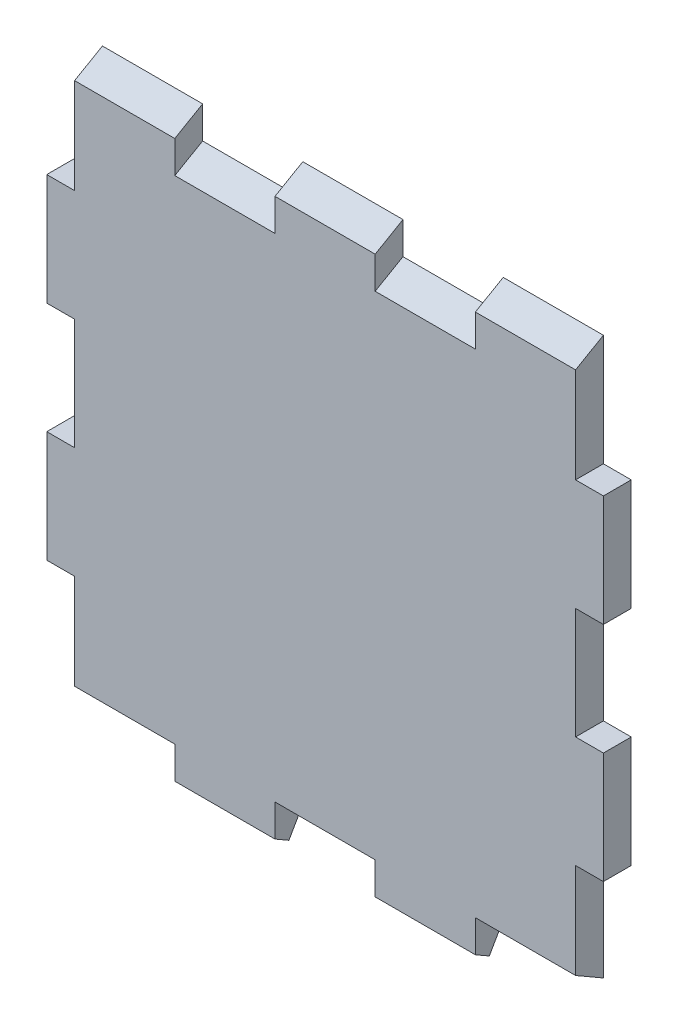
SolidWorks part; units mm, degrees
ref_plane "Front Plane" through (0, 0, 0) normal (0, 0, 1) x (1, 0, 0)
ref_plane "Top Plane" through (0, 0, 0) normal (0, 1, 0) x (1, 0, 0)
ref_plane "Right Plane" through (0, 0, 0) normal (1, 0, 0) x (0, 0, -1)
sketch "Esquisse1" plane through (0, 0, 0) normal (0, 0, 1) x (1, 0, 0)
  line L1 (0, 0) -> (-90, 0)
  line L2 (0, 0) -> (0, -100)
  line L3 (0, -100) -> (-90, -100)
  line L4 (-90, 0) -> (-90, -100)
  line L5 (-45, -100) -> (-45, 0) construction
  line L6 (0, -50) -> (-90, -50) construction
  point P84 (-45, -50)
  dimension "D1" = 100
  dimension "D2" = 90
extrude "Boss.-Extru.3" add sketch "Esquisse1" along normal blind 5
sketch "Esquisse5" plane through (0, 0, 0) normal (1, 0, 0) x (0, 0, -1)
  line L0 (0, 0) -> (-5, 0)
  line L1 (-5, -100) -> (-5, 0) construction
  line L2 (-5, 0) -> (-5, -5.7735)
  line L3 (-86.6025, -52.8868) -> (-69.282, -42.8868) construction
  line L4 (-5, -5.7735) -> (0, -2.8868)
  line L5 (0, -100) -> (0, 0) construction
  line L6 (0, -2.8868) -> (0, 0)
extrude "Enlèv. mat.-Extru.3" cut sketch "Esquisse5" against normal through all
sketch "Esquisse6" plane through (0, 0, 0) normal (1, 0, 0) x (0, 0, -1)
  line L0 (0, -100) -> (-5, -100)
  line L1 (-5, -100) -> (0, -102.8868)
  line L2 (0, -102.8868) -> (0, -100)
extrude "Boss.-Extru.4" add sketch "Esquisse6" against normal through all
sketch "Esquisse7" plane through (0, 0, 5) normal (0, 0, 1) x (1, 0, 0)
  line L0 (-90, -5.7735) -> (0, -5.7735) construction
  line L1 (-72, -11.547) -> (-54, -11.547)
  line L2 (-72, -11.547) -> (-72, -5.7735)
  line L3 (-72, -5.7735) -> (-54, -5.7735)
  line L4 (-54, -11.547) -> (-54, -5.7735)
  line L5 (-63, -5.7735) -> (-63, -11.547) construction
  line L6 (-72, -8.6603) -> (-54, -8.6603) construction
  line L7 (-36, -11.547) -> (-18, -11.547)
  line L8 (-36, -11.547) -> (-36, -5.7735)
  line L9 (-36, -5.7735) -> (-18, -5.7735)
  line L10 (-18, -11.547) -> (-18, -5.7735)
  line L11 (-27, -5.7735) -> (-27, -11.547) construction
  line L12 (-36, -8.6603) -> (-18, -8.6603) construction
  point P10 (-63, 2.6068)
  point P370 (-27, -8.6603)
  point P420 (-63, -8.6603)
  dimension "D1" = 18
  dimension "D2" = 18
extrude "Enlèv. mat.-Extru.4" cut sketch "Esquisse7" against normal through all
sketch "Esquisse8" plane through (0, -5.7735, 0) normal (0, -1, 0) x (1, 0, 0)
  line L4 (-54, 5) -> (-72, 5)
  line L5 (-72, 5) -> (-72, 0)
  line L6 (-72, 0) -> (-54, 0)
  line L7 (-54, 0) -> (-54, 5)
  line L8 (-54, 5) -> (-72, 5)
  line L9 (-72, 5) -> (-72, 0)
  line L10 (-72, 0) -> (-54, 0)
  line L11 (-54, 0) -> (-54, 5)
  dimension "D1" = 0
extrude "Enlèv. mat.-Extru.5" cut sketch "Esquisse8" against normal through all
sketch "Esquisse9" plane through (0, -5.7735, 0) normal (0, -1, 0) x (1, 0, 0)
  line L4 (-18, 5) -> (-36, 5)
  line L5 (-36, 5) -> (-36, 0)
  line L6 (-36, 0) -> (-18, 0)
  line L7 (-18, 0) -> (-18, 5)
  line L8 (-18, 5) -> (-36, 5)
  line L9 (-36, 5) -> (-36, 0)
  line L10 (-36, 0) -> (-18, 0)
  line L11 (-18, 0) -> (-18, 5)
  dimension "D1" = 0
extrude "Enlèv. mat.-Extru.6" cut sketch "Esquisse9" against normal through all
sketch "Esquisse10" plane through (-36, 0, 0) normal (1, 0, 0) x (0, 0, -1)
  line L0 (0, -11.547) -> (-5, -11.547)
  line L1 (-5, -11.547) -> (0, -8.6638)
  line L2 (0, -2.8868) -> (0, -11.547) construction
  line L3 (0, -2.8868) -> (0, -102.8868) construction
  line L4 (0, -8.6638) -> (0, -11.547)
  point P4 (0, -9.6473)
  point P10 (0, -8.6638)
extrude "Boss.-Extru.5" add sketch "Esquisse10" against normal through all and the other way through all
sketch "Esquisse11" plane through (0, 0, 5) normal (0, 0, 1) x (1, 0, 0)
  line L0 (-90, -100) -> (0, -100) construction
  line L1 (-72, -100) -> (-54, -100)
  line L2 (-72, -100) -> (-72, -113)
  line L3 (-72, -113) -> (-54, -113)
  line L4 (-54, -100) -> (-54, -113)
  line L5 (-63, -113) -> (-63, -100) construction
  line L6 (-72, -106.5) -> (-54, -106.5) construction
  line L7 (-90, -100) -> (-90, -102.8868) construction
  line L8 (-36, -100) -> (-18, -100)
  line L9 (-36, -100) -> (-36, -113)
  line L10 (-36, -113) -> (-18, -113)
  line L11 (-18, -100) -> (-18, -113)
  line L12 (-27, -113) -> (-27, -100) construction
  line L13 (-36, -106.5) -> (-18, -106.5) construction
  point P92 (-63, -106.5)
  point P99 (-27, -106.5)
  dimension "D1" = 18
  dimension "D2" = 18
  dimension "D3" = 18
  dimension "D4" = 18
  dimension "D5" = 13
extrude "Boss.-Extru.6" add sketch "Esquisse11" against normal through all
sketch "Esquisse12" plane through (-72, 0, 0) normal (-1, 0, 0) x (0, 0, 1)
  line L0 (0, -102.8868) -> (2.5, -107.2169)
  line L1 (2.5, -107.2169) -> (5, -105.7735)
  line L2 (89.1025, -57.2169) -> (71.782, -67.2169) construction
  line L4 (5, -113) -> (5, -100)
  line L5 (5, -100) -> (0, -102.8868)
  line L6 (0, -102.8868) -> (0, -113)
  line L7 (0, -113) -> (5, -113)
  line L8 (5, -113) -> (5, -105.7735)
  line L10 (0, -102.8868) -> (0, -113)
  line L11 (0, -113) -> (5, -113)
  dimension "D1" = 0
extrude "Enlèv. mat.-Extru.7" cut sketch "Esquisse12" against normal through all
sketch "Esquisse13" plane through (0, 0, 0) normal (0, 0, -1) x (-1, 0, 0)
  line L0 (90, -2.8868) -> (90, -102.8868) construction
  line L1 (90, -22.8868) -> (95, -22.8868)
  line L2 (90, -22.8868) -> (90, -42.8868)
  line L3 (90, -42.8868) -> (95, -42.8868)
  line L4 (95, -22.8868) -> (95, -42.8868)
  line L5 (92.5, -42.8868) -> (92.5, -22.8868) construction
  line L6 (90, -32.8868) -> (95, -32.8868) construction
  line L7 (95, -2.8868) -> (95, -22.8868) construction
  line L8 (90, -2.8868) -> (72, -2.8868) construction
  line L9 (90, -62.8868) -> (95, -62.8868)
  line L10 (90, -62.8868) -> (90, -82.8868)
  line L11 (90, -82.8868) -> (95, -82.8868)
  line L12 (95, -62.8868) -> (95, -82.8868)
  line L13 (92.5, -82.8868) -> (92.5, -62.8868) construction
  line L14 (90, -72.8868) -> (95, -72.8868) construction
  line L15 (45, -2.8868) -> (45, -102.8868) construction
  line L16 (54, -2.8868) -> (36, -2.8868) construction
  line L17 (54, -102.8868) -> (36, -102.8868) construction
  line L18 (0, -72.8868) -> (-5, -72.8868) construction
  line L19 (-2.5, -82.8868) -> (-2.5, -62.8868) construction
  line L20 (0, -32.8868) -> (-5, -32.8868) construction
  line L21 (-2.5, -42.8868) -> (-2.5, -22.8868) construction
  line L22 (-5, -62.8868) -> (-5, -82.8868)
  line L23 (0, -82.8868) -> (-5, -82.8868)
  line L24 (0, -62.8868) -> (0, -82.8868)
  line L25 (0, -62.8868) -> (-5, -62.8868)
  line L26 (-5, -22.8868) -> (-5, -42.8868)
  line L27 (0, -42.8868) -> (-5, -42.8868)
  line L28 (0, -22.8868) -> (0, -42.8868)
  line L29 (0, -22.8868) -> (-5, -22.8868)
  point P40 (-2.5, -72.8868)
  point P41 (-2.5, -32.8868)
  point P68 (92.5, -32.8868)
  point P109 (92.5, -72.8868)
  dimension "D1" = 20
  dimension "D2" = 20
  dimension "D3" = 20
  dimension "D4" = 20
extrude "Boss.-Extru.7" add sketch "Esquisse13" against normal through all
